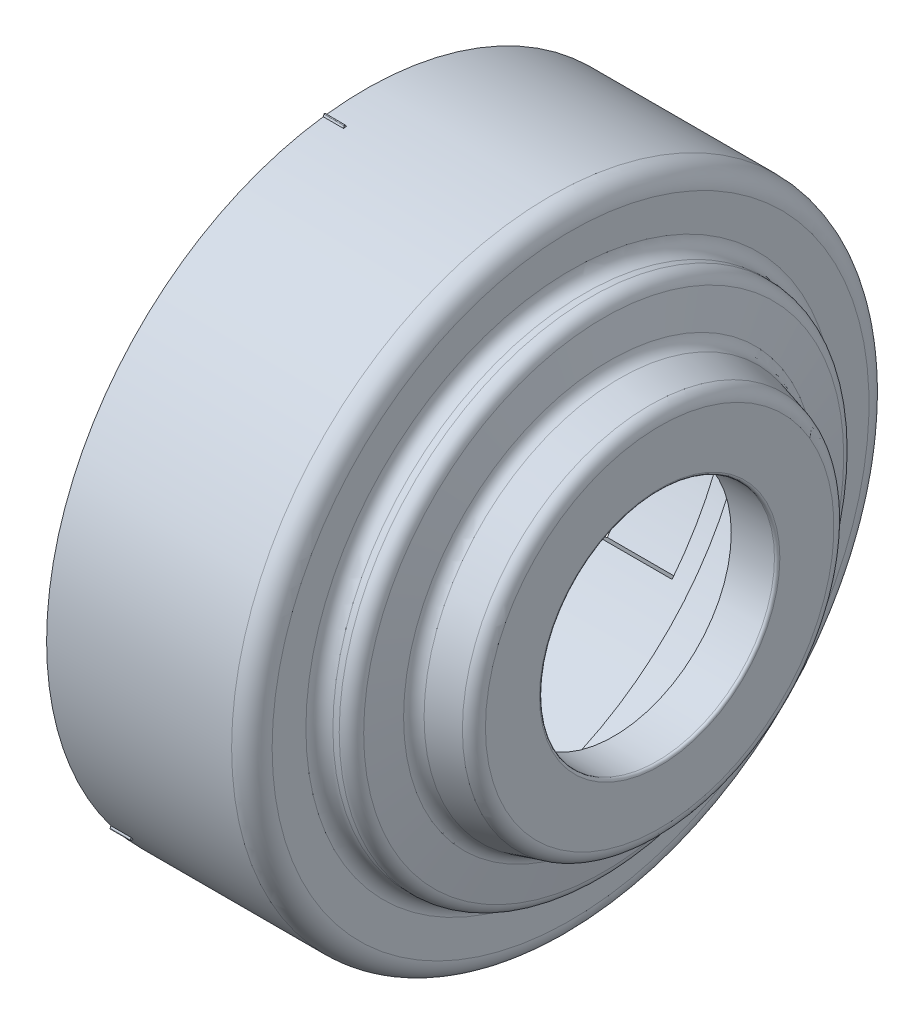
SolidWorks part; units mm, degrees
ref_plane "前视基准面" through (0, 0, 0) normal (0, 0, 1) x (1, 0, 0)
ref_plane "上视基准面" through (0, 0, 0) normal (0, 1, 0) x (1, 0, 0)
ref_plane "右视基准面" through (0, 0, 0) normal (1, 0, 0) x (0, 0, -1)
sketch "草图2" plane through (0, 0, 0) normal (0, 0, 1) x (1, 0, 0)
  line L0 (-36.9366, 0) -> (44.5849, 0) construction
  line L1 (0, 36.0368) -> (0, -37.1166) construction
  line L2 (-14, 22) -> (-6.9, 22)
  line L3 (-6.9, 22) -> (-6.9, 21.6)
  line L4 (-6.9, 21.6) -> (0, 21.6)
  line L5 (0, 21.6) -> (0, 17.4)
  line L6 (0, 17.4) -> (2.5, 17.4)
  line L9 (6.6, 12.75) -> (6.6, 9.4)
  line L10 (6.6, 9.4) -> (4.4, 9.4)
  line L11 (4.4, 9.4) -> (4.4, 8.7)
  line L12 (4.4, 8.7) -> (7.8, 8.7)
  line L13 (-14, 22) -> (-14, 23.6)
  line L14 (-14, 23.6) -> (1.2, 23.6)
  line L15 (1.2, 23.6) -> (1.2, 18.6)
  line L16 (1.2, 18.6) -> (3.5069, 18.6)
  line L19 (7.8, 13.6708) -> (7.8, 8.7)
  line L20 (2.5, 17.4) -> (3.1573, 13.6725)
  line L21 (3.5069, 18.6) -> (4.2063, 14.6337)
  line L22 (6.6, 12.75) -> (3.1573, 13.6725)
  line L23 (7.8, 13.6708) -> (4.2063, 14.6337)
  dimension "D1" = 44
  dimension "D2" = 0.4
  dimension "D3" = 7.1
  dimension "D4" = 14
  dimension "D5" = 34.8
  dimension "D6" = 2.5
  dimension "D7" = 18.8
  dimension "D8" = 0.7
  dimension "D9" = 4.4
  dimension "D10" = 2.2
  dimension "D11" = 25.5
  dimension "D12" = 47.2
  dimension "D13" = 2
  dimension "D14" = 1.2
  dimension "D15" = 10
  dimension "D16" = 105
  dimension "D17" = 1.2
  dimension "D18" = 1.2
  dimension "D19" = 1.2
  dimension "D20" = 1.6
  dimension "D21" = 1.2
revolve "旋转1" add sketch "草图2" angle 360 about L0
fillet "圆角1" radius 0.2 5 edges at (0, 0, 17.4) (0, 0, 21.6) (7.8, 0, 8.7) (2.5, 0, 17.4) (6.6, 0, 12.75)
fillet "圆角2" radius 1 4 edges at (1.2, 0, 18.6) (3.5069, 0, 18.6) (7.8, 0, 13.6708) (4.2063, 0, 14.6337)
fillet "圆角3" radius 1.5 2 edges at (1.2, 0, 23.6) (3.1573, 0, 13.6725)
sketch "草图3" plane through (-14, 0, 0) normal (-1, 0, 0) x (0, 0, 1)
  line L0 (0, 27.1942) -> (0, -25.474) construction
  line L1 (-27.7353, 0) -> (28.2343, 0) construction
  line L2 (-0.5, 22.6) -> (0.5, 22.6)
  line L3 (-0.5, 22.6) -> (-0.5, 21.9943)
  line L4 (0.5, 22.6) -> (0.5, 21.9943)
  circle A0 centre (0, 0) radius 22 construction
  arc A1 (0.5, 21.9943) -> (-0.5, 21.9943) centre (0, 0) ccw
  point P7 (0, 22)
  point P14 (0, 22.6)
  dimension "D1" = 1
  dimension "D2" = 0.6
extrude "切除-拉伸1" cut sketch "草图3" against normal blind 1
sketch "草图4" plane through (-14, 0, 0) normal (-1, 0, 0) x (0, 0, 1)
  line L0 (0, 29.159) -> (0, -31.1439) construction
  line L1 (-35.4917, 0) -> (32.6562, 0) construction
  line L2 (-3.25, 22.5672) -> (-3.25, 21.7586)
  line L3 (3.25, 22.5672) -> (3.25, 21.7586)
  circle A0 centre (0, 0) radius 22 construction
  arc A1 (3.25, 21.7586) -> (-3.25, 21.7586) centre (0, 0) ccw
  arc A2 (3.25, 22.5672) -> (-3.25, 22.5672) centre (0, 0) ccw
  dimension "D2" = 22.8
  dimension "D1" = 6.5
  dimension "D3" = 3.25
extrude "切除-拉伸2" cut sketch "草图4" against normal blind 5.5
sketch "草图5" plane through (0, 0, 0) normal (0, 0, 1) x (1, 0, 0)
  line L0 (16.6242, 0) -> (-23.7431, 0) construction
  line L1 (0, 27.01) -> (0, -27.8633) construction
  line L2 (-8.5, 22.8) -> (-8.5, 21.3419)
  line L3 (-8.5, 21.3419) -> (-10.7, 21.3419)
  line L4 (-10.7, 21.3419) -> (-10.7, 22.8)
  line L5 (-10.7, 22.8) -> (-8.5, 22.8)
  line L7 (-14, -0.1207) -> (-14, 29.419) construction
  line L8 (-14, 21.7586) -> (-14, -22) construction
  dimension "D1" = 3.3
  dimension "D2" = 2.2
  dimension "D3" = 45.6
revolve "切除-旋转1" cut sketch "草图5" angle 24 about L0
ref_plane "基准面1" through (0, 18, 0) normal (0, 1, 0) x (1, 0, 0)
sketch "草图6" plane through (0, 18, 0) normal (0, 1, 0) x (1, 0, 0)
  line L0 (16.0352, 0) -> (-25.287, 0) construction
  line L1 (-10.7, -8.9482) -> (-10.7, -3.25) construction
  line L2 (-10.7, -8.9482) -> (-10.7, -3.25)
  line L3 (-10.7, -3.25) -> (-10.7995, -8.9482)
  line L5 (-10.7, -8.9482) -> (-10.7995, -8.9482)
  dimension "D1" = 1
extrude "切除-拉伸3" cut sketch "草图6" along normal up to surface (2.9707 mm away)
pattern_circular "阵列(圆周)1" count 3 over 360 about axis through (0, 0, 0) along (1, 0, 0) of "切除-拉伸2", "切除-旋转1"
sketch "草图9" plane through (-10.7, 0, 0) normal (1, 0, 0) x (0, 0, -1)
  line L0 (-9.2736, 20.8288) -> (-8.9482, 20.098) construction
  line L1 (-8.9482, 20.9707) -> (-8.9482, 20.098) construction
  line L2 (-9.2736, 20.8288) -> (-8.9482, 20.098)
  line L3 (-8.9482, 20.9707) -> (-8.9482, 20.098)
  arc A0 (-8.9482, 20.9707) -> (-9.2736, 20.8288) centre (0, 0) ccw construction
  arc A1 (-8.9482, 20.9707) -> (-9.2736, 20.8288) centre (0, 0) ccw
extrude "切除-拉伸5" cut sketch "草图9" against normal up to surface (0.0995 mm away)
pattern_circular "阵列(圆周)3" count 3 over 360 about axis through (0, 0, 0) along (1, 0, 0) of "切除-拉伸3"
sketch "草图10" plane through (-10.7, 0, 0) normal (1, 0, 0) x (0, 0, -1)
  line L2 (22.6751, -2.3832) -> (21.8795, -2.2996)
  line L3 (21.8795, -2.2996) -> (22.6352, -2.736)
  line L4 (22.6751, -2.3832) -> (21.8795, -2.2996)
  line L5 (21.8795, -2.2996) -> (22.6352, -2.736)
  arc A1 (22.6352, -2.736) -> (22.6751, -2.3832) centre (0, 0) ccw
  arc A2 (22.6352, -2.736) -> (22.6751, -2.3832) centre (0, 0) ccw
  dimension "D1" = 0
extrude "切除-拉伸6" cut sketch "草图10" against normal up to surface (0.0995 mm away)
sketch "草图11" plane through (-10.7, 0, 0) normal (1, 0, 0) x (0, 0, -1)
  line L2 (-13.4015, -18.4456) -> (-12.9313, -17.7984)
  line L3 (-12.9313, -17.7984) -> (-13.687, -18.2347)
  line L4 (-13.4015, -18.4456) -> (-12.9313, -17.7984)
  line L5 (-12.9313, -17.7984) -> (-13.687, -18.2347)
  arc A1 (-13.687, -18.2347) -> (-13.4015, -18.4456) centre (0, 0) ccw
  arc A2 (-13.687, -18.2347) -> (-13.4015, -18.4456) centre (0, 0) ccw
  dimension "D1" = 0
extrude "切除-拉伸7" cut sketch "草图11" against normal up to surface (0.0995 mm away)
sketch "草图14" plane through (-14, 0, 0) normal (-1, 0, 0) x (0, 0, 1)
  line L0 (0, 28.5305) -> (0, -26.4521) construction
  line L1 (-28.5814, 0) -> (29.2627, 0) construction
  line L2 (3.1, 28.1013) -> (3.1, 18.9957) construction
  line L3 (0, 0) -> (3.036, 23.6893) construction
  line L6 (2.8089, 23.7184) -> (3.3581, 23.648) construction
  line L7 (2.8853, 23.423) -> (2.9729, 23.538)
  line L8 (3.0588, 23.527) -> (3.1147, 23.3936)
  circle A0 centre (0, 0) radius 23.6 construction
  arc A1 (3.1147, 23.3936) -> (2.8853, 23.423) centre (0, 0) ccw
  arc A3 (3.0588, 23.527) -> (2.9729, 23.538) centre (3.0127, 23.5077) ccw
  point P7 (3.1, 23.3955)
  point P15 (3.0254, 23.6069)
  point P16 (3, 23.4085)
  dimension "D4" = 0.05
  dimension "D1" = 3.1
  dimension "D2" = 60
  dimension "D3" = 0.2
  dimension "D5" = 30
extrude "凸台-拉伸2" add sketch "草图14" against normal blind 1.5
pattern_circular "阵列(圆周)7" count 3 over 360 about axis through (0, 0, 0) along (1, 0, 0) of "凸台-拉伸2"
